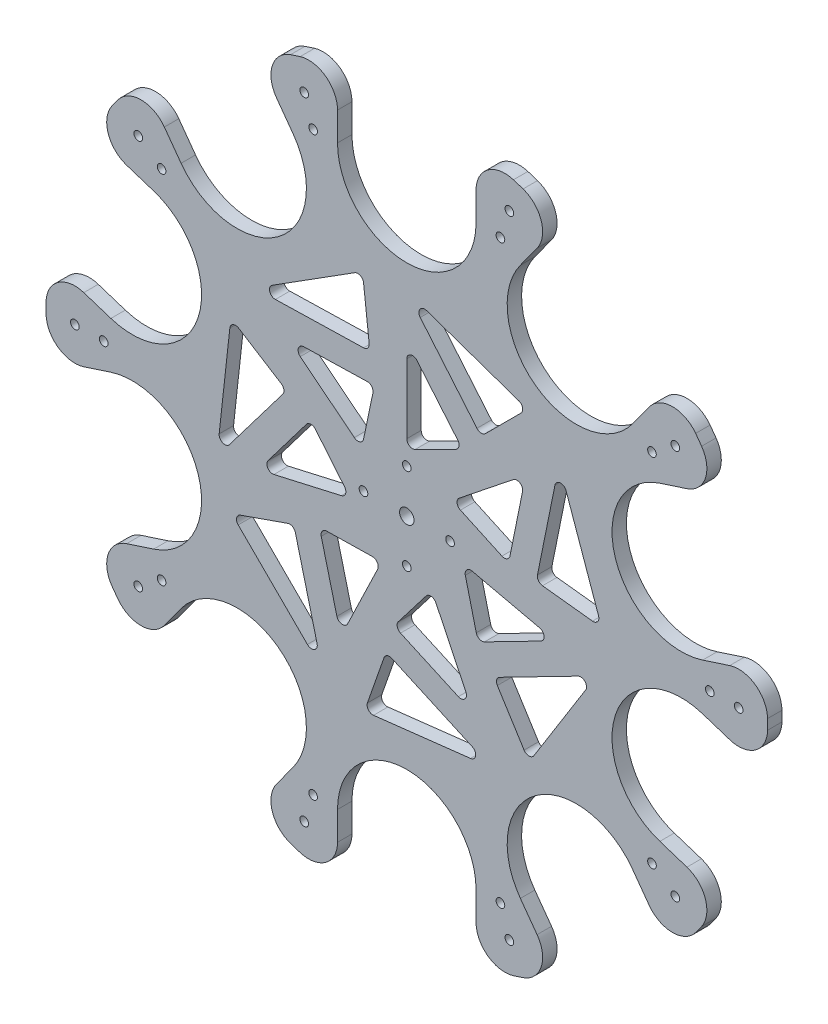
SolidWorks part; units mm, degrees
material "A-玻璃纤维"
ref_plane "前视基准面" through (0, 0, 0) normal (0, 0, 1) x (1, 0, 0)
ref_plane "上视基准面" through (0, 0, 0) normal (0, 1, 0) x (1, 0, 0)
ref_plane "右视基准面" through (0, 0, 0) normal (1, 0, 0) x (0, 0, -1)
sketch "草图1" plane through (0, 0, 0) normal (0, 0, 1) x (1, 0, 0)
  line L20 (-45.1571, 102.9846) -> (-39.3621, 95.0085)
  line L21 (-78.1949, 66.7949) -> (-83.9899, 74.771)
  line L22 (-97.0657, 56.7737) -> (-87.6892, 53.7271)
  line L23 (-102.5221, 8.0763) -> (-111.8985, 11.1229)
  line L24 (-111.8985, -11.1229) -> (-102.5221, -8.0763)
  line L25 (-87.6892, -53.7271) -> (-97.0657, -56.7737)
  line L26 (-83.9899, -74.771) -> (-78.1949, -66.7949)
  line L27 (-39.3621, -95.0085) -> (-45.1571, -102.9846)
  line L28 (-24, -109.859) -> (-24, -100)
  line L29 (24, -100) -> (24, -109.859)
  line L30 (45.1571, -102.9846) -> (39.3621, -95.0085)
  line L31 (78.1949, -66.7949) -> (83.9899, -74.771)
  line L32 (97.0657, -56.7737) -> (87.6892, -53.7271)
  line L33 (102.5221, -8.0763) -> (111.8985, -11.1229)
  line L34 (111.8985, 11.1229) -> (102.5221, 8.0763)
  line L35 (87.6892, 53.7271) -> (97.0657, 56.7737)
  line L36 (83.9899, 74.771) -> (78.1949, 66.7949)
  line L37 (39.3621, 95.0085) -> (45.1571, 102.9846)
  line L38 (24, 109.859) -> (24, 100)
  line L39 (-24, 100) -> (-24, 109.859)
  line L40 (-45.1571, 102.9846) -> (-39.3621, 95.0085)
  line L41 (-78.1949, 66.7949) -> (-83.9899, 74.771)
  line L42 (-97.0657, 56.7737) -> (-87.6892, 53.7271)
  line L43 (-102.5221, 8.0763) -> (-111.8985, 11.1229)
  line L44 (-111.8985, -11.1229) -> (-102.5221, -8.0763)
  line L45 (-87.6892, -53.7271) -> (-97.0657, -56.7737)
  line L46 (-83.9899, -74.771) -> (-78.1949, -66.7949)
  line L47 (-39.3621, -95.0085) -> (-45.1571, -102.9846)
  line L48 (-24, -109.859) -> (-24, -100)
  line L49 (24, -100) -> (24, -109.859)
  line L50 (45.1571, -102.9846) -> (39.3621, -95.0085)
  line L51 (78.1949, -66.7949) -> (83.9899, -74.771)
  line L52 (97.0657, -56.7737) -> (87.6892, -53.7271)
  line L53 (102.5221, -8.0763) -> (111.8985, -11.1229)
  line L54 (111.8985, 11.1229) -> (102.5221, 8.0763)
  line L55 (87.6892, 53.7271) -> (97.0657, 56.7737)
  line L56 (83.9899, 74.771) -> (78.1949, 66.7949)
  line L57 (39.3621, 95.0085) -> (45.1571, 102.9846)
  line L58 (24, 109.859) -> (24, 100)
  line L59 (-24, 100) -> (-24, 109.859)
  arc A0 (-105, 1.5) -> (-105, -1.5) centre (-105, 0) ccw construction
  arc A1 (-105, -1.5) -> (-105, 1.5) centre (-105, 0) ccw construction
  arc A2 (-115, 1.5) -> (-115, -1.5) centre (-115, 0) ccw construction
  arc A3 (-115, -1.5) -> (-115, 1.5) centre (-115, 0) ccw construction
  arc A4 (-105, 1.5) -> (-105, -1.5) centre (-105, 0) ccw
  arc A5 (-105, -1.5) -> (-105, 1.5) centre (-105, 0) ccw
  arc A6 (-115, 1.5) -> (-115, -1.5) centre (-115, 0) ccw
  arc A7 (-115, -1.5) -> (-115, 1.5) centre (-115, 0) ccw
  arc A8 (0, 2.5) -> (0, -2.5) centre (0, 0) ccw construction
  arc A9 (0, -2.5) -> (0, 2.5) centre (0, 0) ccw construction
  arc A10 (0, 2.5) -> (0, -2.5) centre (0, 0) ccw
  arc A11 (0, -2.5) -> (0, 2.5) centre (0, 0) ccw
  arc A12 (-84.0651, 62.931) -> (-85.8285, 60.5039) centre (-84.9468, 61.7175) ccw
  arc A13 (-85.8285, 60.5039) -> (-84.0651, 62.931) centre (-84.9468, 61.7175) ccw
  arc A14 (-92.1553, 68.8088) -> (-93.9186, 66.3818) centre (-93.037, 67.5953) ccw
  arc A15 (-93.9186, 66.3818) -> (-92.1553, 68.8088) centre (-93.037, 67.5953) ccw
  arc A16 (-31.0202, 100.3245) -> (-33.8734, 99.3974) centre (-32.4468, 99.8609) ccw
  arc A17 (-33.8734, 99.3974) -> (-31.0202, 100.3245) centre (-32.4468, 99.8609) ccw
  arc A18 (-34.1104, 109.835) -> (-36.9635, 108.908) centre (-35.537, 109.3715) ccw
  arc A19 (-36.9635, 108.908) -> (-34.1104, 109.835) centre (-35.537, 109.3715) ccw
  arc A20 (33.8734, 99.3974) -> (31.0202, 100.3245) centre (32.4468, 99.8609) ccw
  arc A21 (31.0202, 100.3245) -> (33.8734, 99.3974) centre (32.4468, 99.8609) ccw
  arc A22 (36.9635, 108.908) -> (34.1104, 109.835) centre (35.537, 109.3715) ccw
  arc A23 (34.1104, 109.835) -> (36.9635, 108.908) centre (35.537, 109.3715) ccw
  arc A24 (85.8285, 60.5039) -> (84.0651, 62.931) centre (84.9468, 61.7175) ccw
  arc A25 (84.0651, 62.931) -> (85.8285, 60.5039) centre (84.9468, 61.7175) ccw
  arc A26 (93.9186, 66.3818) -> (92.1553, 68.8088) centre (93.037, 67.5953) ccw
  arc A27 (92.1553, 68.8088) -> (93.9186, 66.3818) centre (93.037, 67.5953) ccw
  arc A28 (105, -1.5) -> (105, 1.5) centre (105, 0) ccw
  arc A29 (105, 1.5) -> (105, -1.5) centre (105, 0) ccw
  arc A30 (115, -1.5) -> (115, 1.5) centre (115, 0) ccw
  arc A31 (115, 1.5) -> (115, -1.5) centre (115, 0) ccw
  arc A32 (84.0651, -62.931) -> (85.8285, -60.5039) centre (84.9468, -61.7175) ccw
  arc A33 (85.8285, -60.5039) -> (84.0651, -62.931) centre (84.9468, -61.7175) ccw
  arc A34 (92.1553, -68.8088) -> (93.9186, -66.3818) centre (93.037, -67.5953) ccw
  arc A35 (93.9186, -66.3818) -> (92.1553, -68.8088) centre (93.037, -67.5953) ccw
  arc A36 (31.0202, -100.3245) -> (33.8734, -99.3974) centre (32.4468, -99.8609) ccw
  arc A37 (33.8734, -99.3974) -> (31.0202, -100.3245) centre (32.4468, -99.8609) ccw
  arc A38 (34.1104, -109.835) -> (36.9635, -108.908) centre (35.537, -109.3715) ccw
  arc A39 (36.9635, -108.908) -> (34.1104, -109.835) centre (35.537, -109.3715) ccw
  arc A40 (-33.8734, -99.3974) -> (-31.0202, -100.3245) centre (-32.4468, -99.8609) ccw
  arc A41 (-31.0202, -100.3245) -> (-33.8734, -99.3974) centre (-32.4468, -99.8609) ccw
  arc A42 (-36.9635, -108.908) -> (-34.1104, -109.835) centre (-35.537, -109.3715) ccw
  arc A43 (-34.1104, -109.835) -> (-36.9635, -108.908) centre (-35.537, -109.3715) ccw
  arc A44 (-85.8285, -60.5039) -> (-84.0651, -62.931) centre (-84.9468, -61.7175) ccw
  arc A45 (-84.0651, -62.931) -> (-85.8285, -60.5039) centre (-84.9468, -61.7175) ccw
  arc A46 (-93.9186, -66.3818) -> (-92.1553, -68.8088) centre (-93.037, -67.5953) ccw
  arc A47 (-92.1553, -68.8088) -> (-93.9186, -66.3818) centre (-93.037, -67.5953) ccw
  arc A48 (0, 13.5) -> (0, 16.5) centre (0, 15) ccw construction
  arc A49 (0, 16.5) -> (0, 13.5) centre (0, 15) ccw construction
  arc A50 (-15, -1.5) -> (-15, 1.5) centre (-15, 0) ccw construction
  arc A51 (-36.9565, 119.412) -> (-40.2901, 118.3288) centre (0, 0) ccw
  arc A52 (-40.2901, 118.3288) -> (-45.1571, 102.9846) centre (-37.0669, 108.8625) ccw
  arc A53 (-78.1949, 66.7949) -> (-39.3621, 95.0085) centre (-58.7785, 80.9017) ccw
  arc A54 (-83.9899, 74.771) -> (-92.0801, 78.8931) centre (-92.0801, 68.8931) ccw
  arc A55 (-92.0801, 78.8931) -> (-100.087, 74.8838) centre (-92.0801, 68.8931) ccw
  arc A56 (-100.087, 74.8838) -> (-102.1473, 72.0481) centre (0, 0) ccw
  arc A57 (-102.1473, 72.0481) -> (-97.0657, 56.7737) centre (-93.9755, 66.2842) ccw
  arc A58 (-102.5221, 8.0763) -> (-87.6892, 53.7271) centre (-95.1057, 30.9017) ccw
  arc A59 (-111.8985, 11.1229) -> (-114.9887, 11.6124) centre (-114.9887, 1.6124) ccw
  arc A60 (-114.9887, 11.6124) -> (-124.9877, 1.7526) centre (-114.9887, 1.6124) ccw
  arc A61 (-124.9877, 1.7526) -> (-124.9877, -1.7526) centre (0, 0) ccw
  arc A62 (-124.9877, -1.7526) -> (-111.8985, -11.1229) centre (-114.9887, -1.6124) ccw
  arc A63 (-95.1057, -6.9017) -> (-102.5221, -8.0763) centre (-95.1057, -30.9017) ccw
  arc A64 (-87.6892, -53.7271) -> (-95.1057, -6.9017) centre (-95.1057, -30.9017) ccw
  arc A65 (-97.0657, -56.7737) -> (-102.1473, -72.0481) centre (-93.9755, -66.2842) ccw
  arc A66 (-102.1473, -72.0481) -> (-100.087, -74.8838) centre (0, 0) ccw
  arc A67 (-100.087, -74.8838) -> (-83.9899, -74.771) centre (-92.0801, -68.8931) ccw
  arc A68 (-58.7785, -56.9017) -> (-78.1949, -66.7949) centre (-58.7785, -80.9017) ccw
  arc A69 (-39.3621, -95.0085) -> (-58.7785, -56.9017) centre (-58.7785, -80.9017) ccw
  arc A70 (-45.1571, -102.9846) -> (-40.2901, -118.3288) centre (-37.0669, -108.8625) ccw
  arc A71 (-40.2901, -118.3288) -> (-36.9565, -119.412) centre (0, 0) ccw
  arc A72 (-36.9565, -119.412) -> (-24, -109.859) centre (-34, -109.859) ccw
  arc A73 (0, -76) -> (-24, -100) centre (0, -100) ccw
  arc A74 (24, -100) -> (0, -76) centre (0, -100) ccw
  arc A75 (24, -109.859) -> (36.9565, -119.412) centre (34, -109.859) ccw
  arc A76 (36.9565, -119.412) -> (40.2901, -118.3288) centre (0, 0) ccw
  arc A77 (40.2901, -118.3288) -> (45.1571, -102.9846) centre (37.0669, -108.8625) ccw
  arc A78 (58.7785, -56.9017) -> (39.3621, -95.0085) centre (58.7785, -80.9017) ccw
  arc A79 (78.1949, -66.7949) -> (58.7785, -56.9017) centre (58.7785, -80.9017) ccw
  arc A80 (83.9899, -74.771) -> (100.087, -74.8838) centre (92.0801, -68.8931) ccw
  arc A81 (100.087, -74.8838) -> (102.1473, -72.0481) centre (0, 0) ccw
  arc A82 (102.1473, -72.0481) -> (97.0657, -56.7737) centre (93.9755, -66.2842) ccw
  arc A83 (95.1057, -6.9017) -> (87.6892, -53.7271) centre (95.1057, -30.9017) ccw
  arc A84 (102.5221, -8.0763) -> (95.1057, -6.9017) centre (95.1057, -30.9017) ccw
  arc A85 (111.8985, -11.1229) -> (124.9877, -1.7526) centre (114.9887, -1.6124) ccw
  arc A86 (124.9877, -1.7526) -> (124.9877, 1.7526) centre (0, 0) ccw
  arc A87 (124.9877, 1.7526) -> (114.9887, 11.6124) centre (114.9887, 1.6124) ccw
  arc A88 (114.9887, 11.6124) -> (111.8985, 11.1229) centre (114.9887, 1.6124) ccw
  arc A89 (87.6892, 53.7271) -> (102.5221, 8.0763) centre (95.1057, 30.9017) ccw
  arc A90 (97.0657, 56.7737) -> (102.1473, 72.0481) centre (93.9755, 66.2842) ccw
  arc A91 (102.1473, 72.0481) -> (100.087, 74.8838) centre (0, 0) ccw
  arc A92 (100.087, 74.8838) -> (92.0801, 78.8931) centre (92.0801, 68.8931) ccw
  arc A93 (92.0801, 78.8931) -> (83.9899, 74.771) centre (92.0801, 68.8931) ccw
  arc A94 (39.3621, 95.0085) -> (78.1949, 66.7949) centre (58.7785, 80.9017) ccw
  arc A95 (45.1571, 102.9846) -> (40.2901, 118.3288) centre (37.0669, 108.8625) ccw
  arc A96 (40.2901, 118.3288) -> (36.9565, 119.412) centre (0, 0) ccw
  arc A97 (36.9565, 119.412) -> (34, 119.859) centre (34, 109.859) ccw
  arc A98 (34, 119.859) -> (24, 109.859) centre (34, 109.859) ccw
  arc A99 (-24, 100) -> (24, 100) centre (0, 100) ccw
  arc A100 (-24, 109.859) -> (-34, 119.859) centre (-34, 109.859) ccw
  arc A101 (-34, 119.859) -> (-36.9565, 119.412) centre (-34, 109.859) ccw
  arc A102 (-36.9565, 119.412) -> (-40.2901, 118.3288) centre (0, 0) ccw
  arc A103 (-40.2901, 118.3288) -> (-45.1571, 102.9846) centre (-37.0669, 108.8625) ccw
  arc A104 (-78.1949, 66.7949) -> (-39.3621, 95.0085) centre (-58.7785, 80.9017) ccw
  arc A105 (-83.9899, 74.771) -> (-92.0801, 78.8931) centre (-92.0801, 68.8931) ccw
  arc A106 (-92.0801, 78.8931) -> (-100.087, 74.8838) centre (-92.0801, 68.8931) ccw
  arc A107 (-100.087, 74.8838) -> (-102.1473, 72.0481) centre (0, 0) ccw
  arc A108 (-102.1473, 72.0481) -> (-97.0657, 56.7737) centre (-93.9755, 66.2842) ccw
  arc A109 (-102.5221, 8.0763) -> (-87.6892, 53.7271) centre (-95.1057, 30.9017) ccw
  arc A110 (-111.8985, 11.1229) -> (-114.9887, 11.6124) centre (-114.9887, 1.6124) ccw
  arc A111 (-114.9887, 11.6124) -> (-124.9877, 1.7526) centre (-114.9887, 1.6124) ccw
  arc A112 (-124.9877, 1.7526) -> (-124.9877, -1.7526) centre (0, 0) ccw
  arc A113 (-124.9877, -1.7526) -> (-111.8985, -11.1229) centre (-114.9887, -1.6124) ccw
  arc A114 (-95.1057, -6.9017) -> (-102.5221, -8.0763) centre (-95.1057, -30.9017) ccw
  arc A115 (-87.6892, -53.7271) -> (-95.1057, -6.9017) centre (-95.1057, -30.9017) ccw
  arc A116 (-97.0657, -56.7737) -> (-102.1473, -72.0481) centre (-93.9755, -66.2842) ccw
  arc A117 (-102.1473, -72.0481) -> (-100.087, -74.8838) centre (0, 0) ccw
  arc A118 (-100.087, -74.8838) -> (-83.9899, -74.771) centre (-92.0801, -68.8931) ccw
  arc A119 (-58.7785, -56.9017) -> (-78.1949, -66.7949) centre (-58.7785, -80.9017) ccw
  arc A120 (-39.3621, -95.0085) -> (-58.7785, -56.9017) centre (-58.7785, -80.9017) ccw
  arc A121 (-45.1571, -102.9846) -> (-40.2901, -118.3288) centre (-37.0669, -108.8625) ccw
  arc A122 (-40.2901, -118.3288) -> (-36.9565, -119.412) centre (0, 0) ccw
  arc A123 (-36.9565, -119.412) -> (-24, -109.859) centre (-34, -109.859) ccw
  arc A124 (0, -76) -> (-24, -100) centre (0, -100) ccw
  arc A125 (24, -100) -> (0, -76) centre (0, -100) ccw
  arc A126 (24, -109.859) -> (36.9565, -119.412) centre (34, -109.859) ccw
  arc A127 (36.9565, -119.412) -> (40.2901, -118.3288) centre (0, 0) ccw
  arc A128 (40.2901, -118.3288) -> (45.1571, -102.9846) centre (37.0669, -108.8625) ccw
  arc A129 (58.7785, -56.9017) -> (39.3621, -95.0085) centre (58.7785, -80.9017) ccw
  arc A130 (78.1949, -66.7949) -> (58.7785, -56.9017) centre (58.7785, -80.9017) ccw
  arc A131 (83.9899, -74.771) -> (100.087, -74.8838) centre (92.0801, -68.8931) ccw
  arc A132 (100.087, -74.8838) -> (102.1473, -72.0481) centre (0, 0) ccw
  arc A133 (102.1473, -72.0481) -> (97.0657, -56.7737) centre (93.9755, -66.2842) ccw
  arc A134 (95.1057, -6.9017) -> (87.6892, -53.7271) centre (95.1057, -30.9017) ccw
  arc A135 (102.5221, -8.0763) -> (95.1057, -6.9017) centre (95.1057, -30.9017) ccw
  arc A136 (111.8985, -11.1229) -> (124.9877, -1.7526) centre (114.9887, -1.6124) ccw
  arc A137 (124.9877, -1.7526) -> (124.9877, 1.7526) centre (0, 0) ccw
  arc A138 (124.9877, 1.7526) -> (114.9887, 11.6124) centre (114.9887, 1.6124) ccw
  arc A139 (114.9887, 11.6124) -> (111.8985, 11.1229) centre (114.9887, 1.6124) ccw
  arc A140 (87.6892, 53.7271) -> (102.5221, 8.0763) centre (95.1057, 30.9017) ccw
  arc A141 (97.0657, 56.7737) -> (102.1473, 72.0481) centre (93.9755, 66.2842) ccw
  arc A142 (102.1473, 72.0481) -> (100.087, 74.8838) centre (0, 0) ccw
  arc A143 (100.087, 74.8838) -> (92.0801, 78.8931) centre (92.0801, 68.8931) ccw
  arc A144 (92.0801, 78.8931) -> (83.9899, 74.771) centre (92.0801, 68.8931) ccw
  arc A145 (39.3621, 95.0085) -> (78.1949, 66.7949) centre (58.7785, 80.9017) ccw
  arc A146 (45.1571, 102.9846) -> (40.2901, 118.3288) centre (37.0669, 108.8625) ccw
  arc A147 (40.2901, 118.3288) -> (36.9565, 119.412) centre (0, 0) ccw
  arc A148 (36.9565, 119.412) -> (34, 119.859) centre (34, 109.859) ccw
  arc A149 (34, 119.859) -> (24, 109.859) centre (34, 109.859) ccw
  arc A150 (-24, 100) -> (24, 100) centre (0, 100) ccw
  arc A151 (-24, 109.859) -> (-34, 119.859) centre (-34, 109.859) ccw
  arc A152 (-34, 119.859) -> (-36.9565, 119.412) centre (-34, 109.859) ccw
  arc A153 (-15, 1.5) -> (-15, -1.5) centre (-15, 0) ccw construction
  arc A154 (0, -13.5) -> (0, -16.5) centre (0, -15) ccw construction
  arc A155 (0, -16.5) -> (0, -13.5) centre (0, -15) ccw construction
  arc A156 (15, -1.5) -> (15, 1.5) centre (15, 0) ccw construction
  arc A157 (15, 1.5) -> (15, -1.5) centre (15, 0) ccw construction
  arc A158 (15, 1.5) -> (15, -1.5) centre (15, 0) ccw
  arc A159 (15, -1.5) -> (15, 1.5) centre (15, 0) ccw
  arc A160 (0, -16.5) -> (0, -13.5) centre (0, -15) ccw
  arc A161 (0, -13.5) -> (0, -16.5) centre (0, -15) ccw
  arc A162 (-15, 1.5) -> (-15, -1.5) centre (-15, 0) ccw
  arc A163 (-15, -1.5) -> (-15, 1.5) centre (-15, 0) ccw
  arc A164 (0, 16.5) -> (0, 13.5) centre (0, 15) ccw
  arc A165 (0, 13.5) -> (0, 16.5) centre (0, 15) ccw
  point P208 (0, 0)
  dimension "D1" = 0
  dimension "D2" = 10
extrude "凸台-拉伸1" add sketch "草图1" along normal blind 5
sketch "草图2" plane through (0, 0, 5) normal (0, 0, 1) x (1, 0, 0)
  line L0 (0, 0) -> (0, 67.5) construction
  line L1 (0, 0) -> (47.7297, 47.7297) construction
  line L2 (2.8998, 21.4608) -> (17.0275, 28.5778)
  line L3 (17.6598, 31.6496) -> (3.5321, 48.4863)
  line L4 (0, 47.2007) -> (0, 23.247)
  line L5 (4.6589, 61.9478) -> (24.3085, 38.5302)
  line L6 (27.2548, 38.4016) -> (39.5731, 50.7198)
  line L7 (38.8149, 54.0234) -> (6.8469, 65.1227)
  line L8 (18.5867, 11.1134) -> (32.9595, 4.5053)
  line L9 (35.7553, 5.9262) -> (40.1103, 27.4692)
  line L10 (36.903, 29.4292) -> (18.1752, 14.4942)
  line L11 (51.3375, 34.9814) -> (45.2803, 5.018)
  line L12 (47.0167, 2.6343) -> (64.3277, 0.6838)
  line L13 (66.4378, 3.3363) -> (55.184, 35.2502)
  line L14 (20.2775, -7.6026) -> (24.0723, -22.9598)
  line L15 (26.9264, -24.2597) -> (46.4847, -14.2328)
  line L16 (46.0173, -10.5032) -> (22.6641, -5.1729)
  line L17 (59.3579, -18.3267) -> (32.155, -32.2729)
  line L18 (31.374, -35.1167) -> (40.6423, -49.8671)
  line L19 (44.0318, -49.863) -> (61.9664, -21.1664)
  line L20 (6.6989, -20.5937) -> (-2.9418, -33.1357)
  line L21 (-2.1787, -36.1776) -> (17.8551, -45.2172)
  line L22 (20.4796, -42.5264) -> (10.0865, -20.9448)
  line L23 (22.6807, -57.8344) -> (-5.1836, -45.2616)
  line L24 (-7.894, -46.4241) -> (-13.6476, -62.8671)
  line L25 (-11.5311, -65.5145) -> (22.0868, -61.6443)
  line L26 (-11.9241, -18.0773) -> (-27.7407, -18.3598)
  line L27 (-29.6432, -20.853) -> (-24.2197, -42.1521)
  line L28 (-20.4796, -42.5264) -> (-10.0865, -20.9448)
  line L29 (-31.0756, -53.7916) -> (-38.6189, -24.1674)
  line L30 (-41.2176, -22.7732) -> (-57.6606, -28.5268)
  line L31 (-58.4108, -31.8322) -> (-34.4246, -55.7028)
  line L32 (-21.568, -1.9484) -> (-31.6503, 10.2414)
  line L33 (-34.7857, 10.1744) -> (-48.0566, -7.3457)
  line L34 (-46.0173, -10.5032) -> (-22.6641, -5.1729)
  line L35 (-61.4313, -9.2426) -> (-42.9733, 15.1253)
  line L36 (-43.5035, 18.0264) -> (-58.254, 27.2947)
  line L37 (-61.306, 25.8204) -> (-65.0135, -7.8159)
  line L38 (-14.9707, 15.6477) -> (-11.7266, 31.1306)
  line L39 (-13.7339, 33.5402) -> (-35.7059, 32.9922)
  line L40 (-36.903, 29.4292) -> (-18.1752, 14.4942)
  line L41 (-45.528, 42.2663) -> (-14.968, 43.0284)
  line L42 (-13.0304, 45.2517) -> (-14.9809, 62.5627)
  line L43 (-18.0365, 64.0297) -> (-46.646, 45.9565)
  circle A0 centre (0, 0) radius 67.5 construction
  arc A1 (39.5731, 50.7198) -> (38.8149, 54.0234) centre (38.1589, 52.134) ccw
  arc A2 (6.8469, 65.1227) -> (4.6589, 61.9478) centre (6.1909, 63.2334) ccw
  arc A3 (24.3085, 38.5302) -> (27.2548, 38.4016) centre (25.8406, 39.8158) ccw
  arc A4 (17.0275, 28.5778) -> (17.6598, 31.6496) centre (16.1277, 30.364) ccw
  arc A5 (2.8998, 21.4608) -> (0, 23.247) centre (2, 23.247) cw
  arc A6 (3.5321, 48.4863) -> (0, 47.2007) centre (2, 47.2007) ccw
  arc A7 (64.3277, 0.6838) -> (66.4378, 3.3363) centre (64.5517, 2.6712) ccw
  arc A8 (55.184, 35.2502) -> (51.3375, 34.9814) centre (53.2978, 34.5851) ccw
  arc A9 (45.2803, 5.018) -> (47.0167, 2.6343) centre (47.2406, 4.6217) ccw
  arc A10 (32.9595, 4.5053) -> (35.7553, 5.9262) centre (33.795, 6.3225) ccw
  arc A11 (18.5867, 11.1134) -> (18.1752, 14.4942) centre (19.4222, 12.9306) cw
  arc A12 (40.1103, 27.4692) -> (36.903, 29.4292) centre (38.15, 27.8655) ccw
  arc A13 (40.6423, -49.8671) -> (44.0318, -49.863) centre (42.3358, -48.803) ccw
  arc A14 (61.9664, -21.1664) -> (59.3579, -18.3267) centre (60.2704, -20.1065) ccw
  arc A15 (32.155, -32.2729) -> (31.374, -35.1167) centre (33.0674, -34.0526) ccw
  arc A16 (24.0723, -22.9598) -> (26.9264, -24.2597) centre (26.0139, -22.48) ccw
  arc A17 (20.2775, -7.6026) -> (22.6641, -5.1729) centre (22.2191, -7.1228) cw
  arc A18 (46.4847, -14.2328) -> (46.0173, -10.5032) centre (45.5723, -12.453) ccw
  arc A19 (-13.6476, -62.8671) -> (-11.5311, -65.5145) centre (-11.7598, -63.5276) ccw
  arc A20 (22.0868, -61.6443) -> (22.6807, -57.8344) centre (21.8581, -59.6574) ccw
  arc A21 (-5.1836, -45.2616) -> (-7.894, -46.4241) centre (-6.0062, -47.0846) ccw
  arc A22 (-2.9418, -33.1357) -> (-2.1787, -36.1776) centre (-1.3561, -34.3546) ccw
  arc A23 (6.6989, -20.5937) -> (10.0865, -20.9448) centre (8.2845, -21.8126) cw
  arc A24 (17.8551, -45.2172) -> (20.4796, -42.5264) centre (18.6777, -43.3942) ccw
  arc A25 (-57.6606, -28.5268) -> (-58.4108, -31.8322) centre (-57, -30.4146) ccw
  arc A26 (-34.4246, -55.7028) -> (-31.0756, -53.7916) centre (-33.0138, -54.2851) ccw
  arc A27 (-38.6189, -24.1674) -> (-41.2176, -22.7732) centre (-40.557, -24.6609) ccw
  arc A28 (-27.7407, -18.3598) -> (-29.6432, -20.853) centre (-27.705, -20.3594) ccw
  arc A29 (-11.9241, -18.0773) -> (-10.0865, -20.9448) centre (-11.8884, -20.077) cw
  arc A30 (-24.2197, -42.1521) -> (-20.4796, -42.5264) centre (-22.2816, -41.6586) ccw
  arc A31 (-58.254, 27.2947) -> (-61.306, 25.8204) centre (-59.318, 25.6012) ccw
  arc A32 (-65.0135, -7.8159) -> (-61.4313, -9.2426) centre (-63.0256, -8.035) ccw
  arc A33 (-42.9733, 15.1253) -> (-43.5035, 18.0264) centre (-44.5676, 16.3329) ccw
  arc A34 (-31.6503, 10.2414) -> (-34.7857, 10.1744) centre (-33.1914, 8.9667) ccw
  arc A35 (-21.568, -1.9484) -> (-22.6641, -5.1729) centre (-23.1092, -3.2231) cw
  arc A36 (-48.0566, -7.3457) -> (-46.0173, -10.5032) centre (-46.4624, -8.5533) ccw
  arc A37 (-14.9809, 62.5627) -> (-18.0365, 64.0297) centre (-16.9683, 62.3388) ccw
  arc A38 (-46.646, 45.9565) -> (-45.528, 42.2663) centre (-45.5778, 44.2656) ccw
  arc A39 (-14.968, 43.0284) -> (-13.0304, 45.2517) centre (-15.0179, 45.0278) ccw
  arc A40 (-11.7266, 31.1306) -> (-13.7339, 33.5402) centre (-13.684, 31.5408) ccw
  arc A41 (-14.9707, 15.6477) -> (-18.1752, 14.4942) centre (-16.9282, 16.0579) cw
  arc A42 (-35.7059, 32.9922) -> (-36.903, 29.4292) centre (-35.656, 30.9928) ccw
  point P17 (41.8298, 52.9766)
  point P23 (25.7115, 36.8582)
  point P26 (19.2836, 29.7144)
  point P29 (0, 20)
  point P32 (0, 52.6957)
  point P138 (0, 0)
  dimension "D1" = 135
  dimension "D7" = 2
  dimension "D2" = 45
  dimension "D3" = 20
  dimension "D4" = 30
  dimension "D5" = 40
  dimension "D6" = 40
  dimension "D8" = 7
extrude "切除-拉伸2" cut sketch "草图2" against normal blind 10
